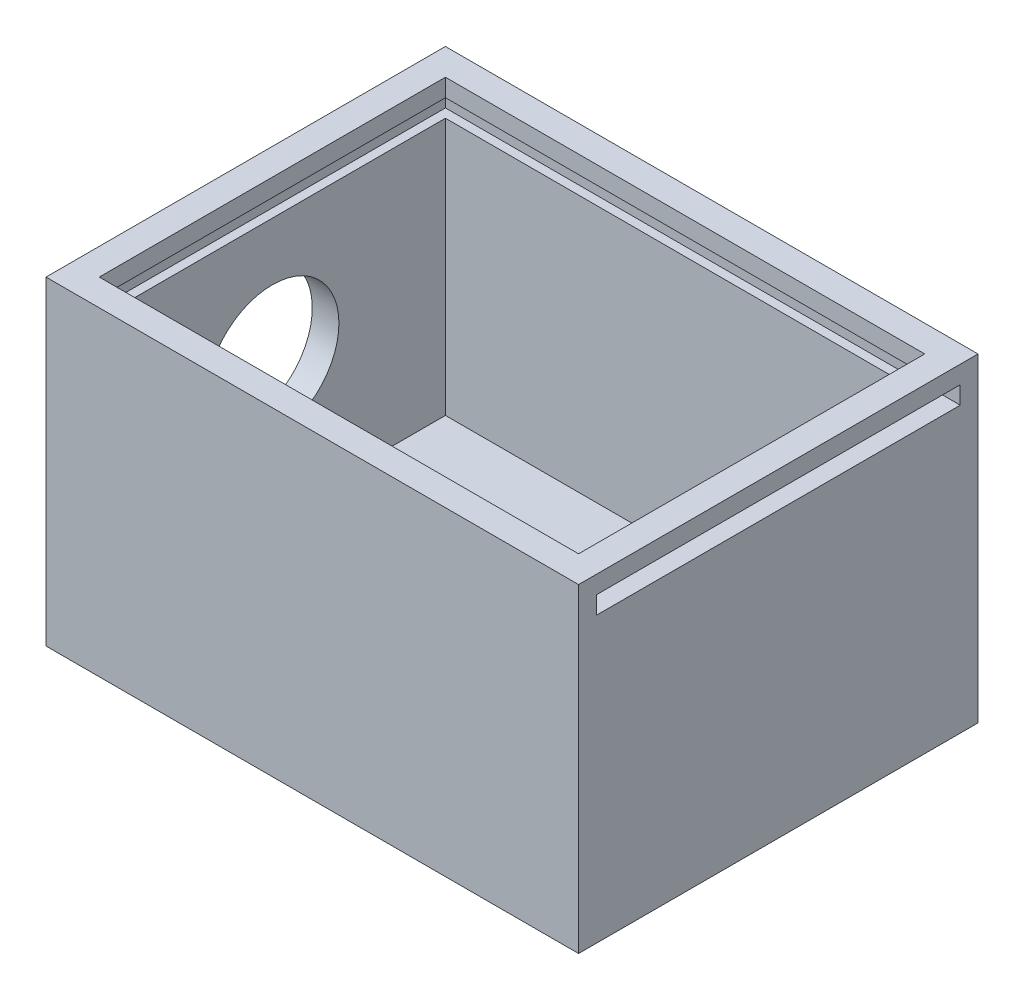
SolidWorks part; units mm, degrees
ref_plane "Front Plane" through (0, 0, 0) normal (0, 0, 1) x (1, 0, 0)
ref_plane "Top Plane" through (0, 0, 0) normal (0, 1, 0) x (1, 0, 0)
ref_plane "Right Plane" through (0, 0, 0) normal (1, 0, 0) x (0, 0, -1)
sketch "Sketch1" plane through (0, 0, 0) normal (0, 0, 1) x (1, 0, 0)
  line L1 (0, 0) -> (60, 0)
  line L2 (0, 0) -> (0, -36)
  line L3 (0, -36) -> (60, -36)
  line L4 (60, 0) -> (60, -36)
  dimension "D1" = 60
  dimension "D2" = 36
extrude "Boss-Extrude1" add sketch "Sketch1" along normal blind 45
shell "Shell1" thickness 3
sketch "Sketch2" plane through (60, 0, 0) normal (1, 0, 0) x (0, 0, -1)
  line L0 (-45, -36) -> (-45, 0) construction
  line L1 (-43, -2) -> (-2, -2)
  line L2 (-43, -2) -> (-43, -4)
  line L3 (-43, -4) -> (-2, -4)
  line L4 (-2, -2) -> (-2, -4)
  line L7 (-45, 0) -> (0, 0) construction
  dimension "D1" = 41
  dimension "D2" = 2
  dimension "D3" = 2
  dimension "D4" = 2
extrude "Cut-Extrude1" cut sketch "Sketch2" against normal blind 58
sketch "Sketch3" plane through (0, 0, 0) normal (-1, 0, 0) x (0, 0, 1)
  line L0 (22.5, 0) -> (22.5, -36) construction
  line L1 (45, 0) -> (0, 0) construction
  line L2 (45, -36) -> (0, -36) construction
  line L3 (0, -18) -> (45, -18) construction
  line L4 (0, 0) -> (0, -36) construction
  line L5 (45, 0) -> (45, -36) construction
  circle A0 centre (22.5, -18) radius 7.5
  dimension "D1" = 15
extrude "Cut-Extrude2" cut sketch "Sketch3" against normal blind 48
